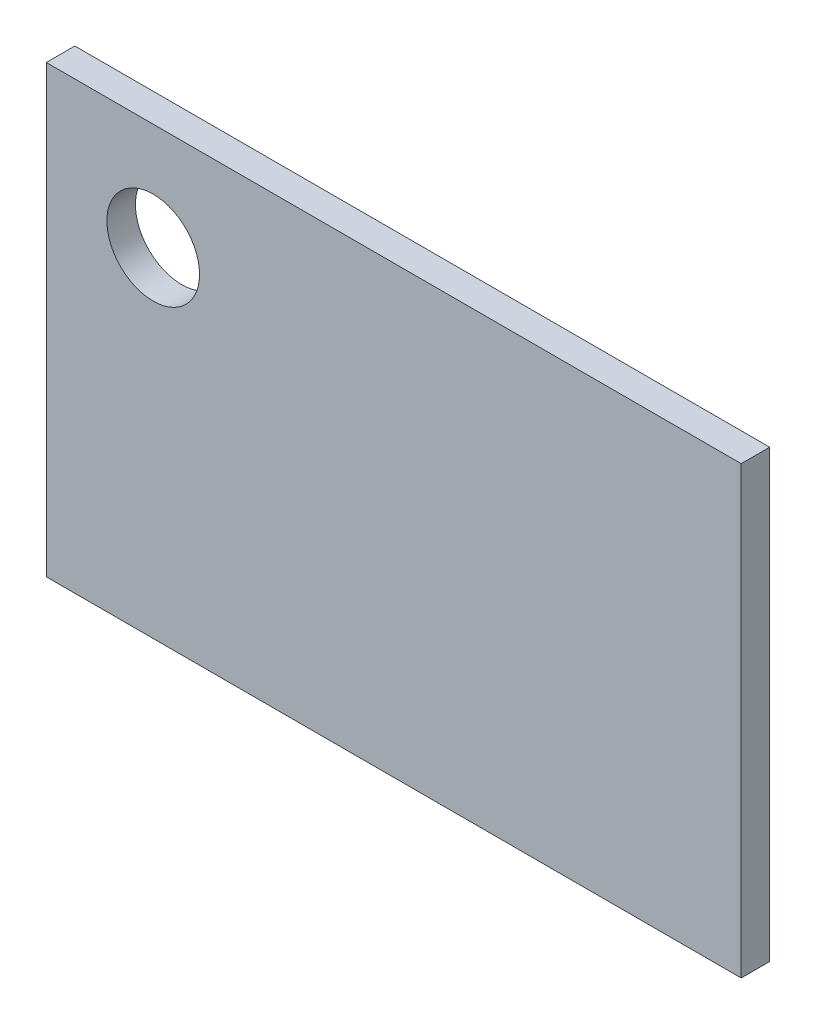
SolidWorks part; units mm, degrees
ref_plane "Plan de face" through (0, 0, 0) normal (0, 0, 1) x (1, 0, 0)
ref_plane "Plan de dessus" through (0, 0, 0) normal (0, 1, 0) x (1, 0, 0)
ref_plane "Plan de droite" through (0, 0, 0) normal (1, 0, 0) x (0, 0, -1)
sketch "Esquisse1" plane through (0, 0, 0) normal (0, 0, 1) x (1, 0, 0)
  line L1 (9.75, -6.25) -> (-9.75, -6.25)
  line L2 (9.75, -6.25) -> (9.75, 6.25)
  line L3 (9.75, 6.25) -> (-9.75, 6.25)
  line L4 (-9.75, -6.25) -> (-9.75, 6.25)
  line L5 (9.75, -6.25) -> (-9.75, 6.25) construction
  line L6 (9.75, 6.25) -> (-9.75, -6.25) construction
  point P0 (0, 0)
  dimension "D1" = 12.5
  dimension "D2" = 19.5
extrude "Boss.-Extru.1" add sketch "Esquisse1" along normal blind 0.8
sketch "Esquisse2" plane through (0, 0, 0.8) normal (0, 0, 1) x (1, 0, 0)
  line L0 (9.75, 6.25) -> (-9.75, 6.25) construction
  line L1 (-9.75, 6.25) -> (-9.75, -6.25) construction
  circle A0 centre (-6.75, 3.25) radius 1.3
  dimension "D3" = 2.6
  dimension "D1" = 3
  dimension "D2" = 3
extrude "Enlèv. mat.-Extru.1" cut sketch "Esquisse2" against normal blind 0.8
